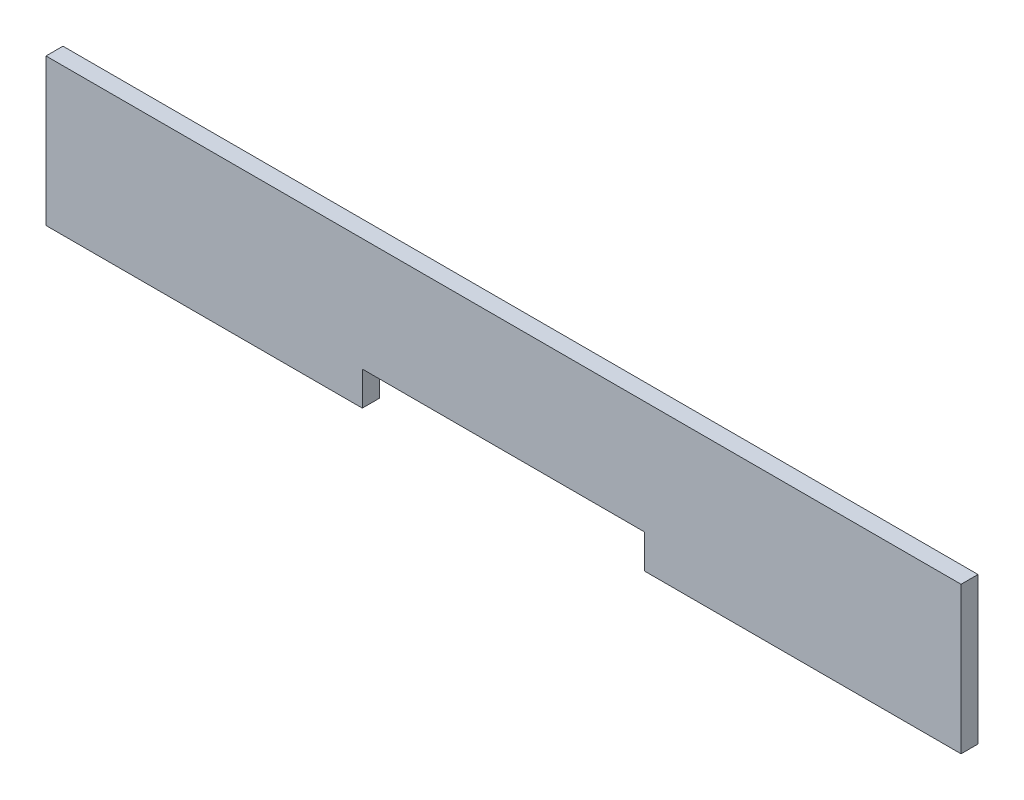
SolidWorks part; units mm, degrees
material "Acrylic (Medium-high impact)"
ref_plane "Alzado" through (0, 0, 0) normal (0, 0, 1) x (1, 0, 0)
ref_plane "Planta" through (0, 0, 0) normal (0, 1, 0) x (1, 0, 0)
ref_plane "Vista lateral" through (0, 0, 0) normal (1, 0, 0) x (0, 0, -1)
sketch "Sketch1" plane through (0, 0, 0) normal (0, 0, 1) x (1, 0, 0)
  line L0 (0, 0) -> (56, 0)
  line L1 (56, 0) -> (56, 6)
  line L2 (56, 6) -> (106, 6)
  line L3 (106, 6) -> (106, 0)
  line L4 (106, 0) -> (162, 0)
  line L5 (162, 0) -> (162, 26)
  line L6 (162, 26) -> (0, 26)
  line L7 (0, 26) -> (0, 0)
  dimension "D1" = 162
  dimension "D2" = 56
  dimension "D3" = 6
  dimension "D4" = 26
extrude "Boss-Extrude1" add sketch "Sketch1" along normal blind 3
